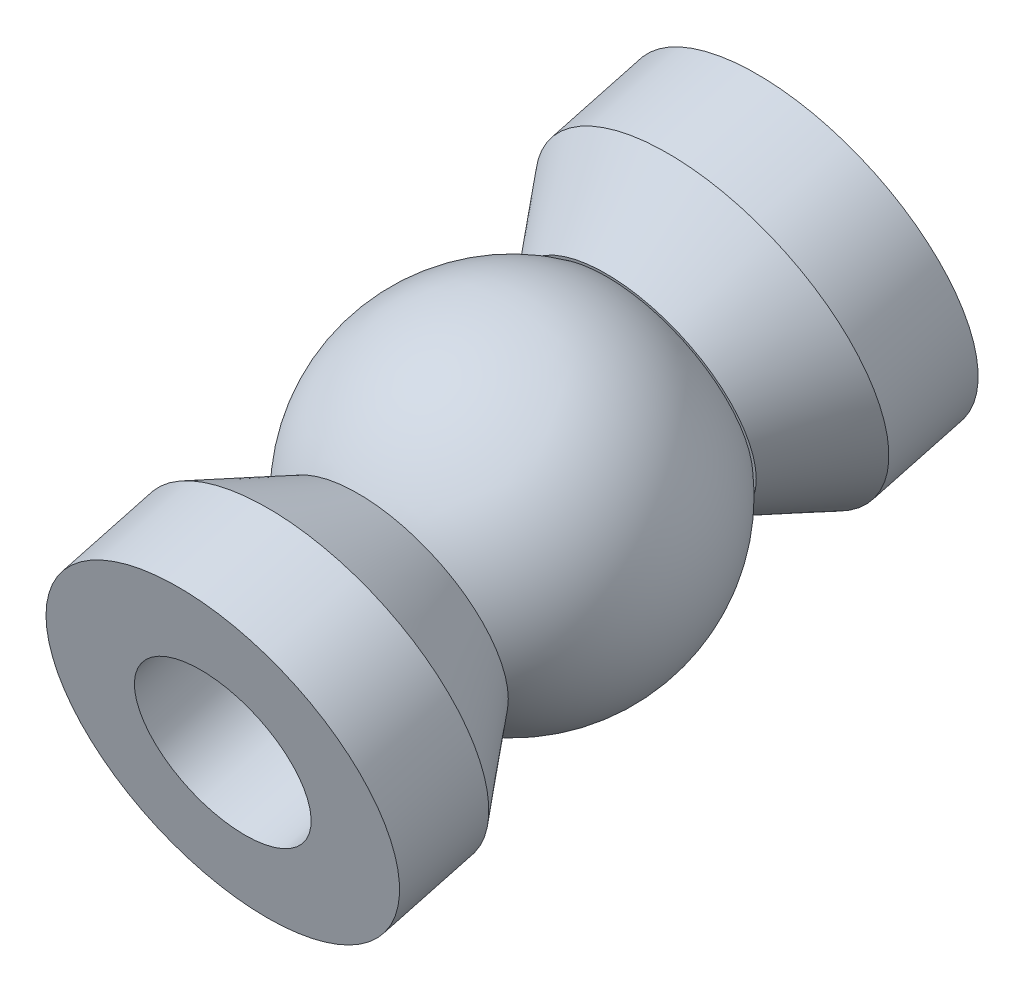
SolidWorks part; units mm, degrees
material "Alloy Steel"
ref_plane "X-Y Datum" through (0, 0, 0) normal (0, 0, 1) x (1, 0, 0)
ref_plane "X-Z Datum" through (0, 0, 0) normal (0, 1, 0) x (1, 0, 0)
ref_plane "Y-Z Datum" through (0, 0, 0) normal (1, 0, 0) x (0, 0, -1)
sketch "Sketch1" plane through (0, 0, 0) normal (1, 0, 0) x (0, 0, -1)
  line L0 (25.353, -33.2172) -> (-48270.9384, -12974.1695) construction
  line L1 (32.2801, -31.5492) -> (-12908.6721, 48264.7421) construction
  line L2 (21.7638, -29.1038) -> (17.1636, -30.3364) construction
  line L3 (23.1427, -40.3834) -> (26.4549, -39.4959)
  line L4 (26.4549, -39.4959) -> (28.7504, -36.7772)
  line L5 (28.7504, -36.7772) -> (28.7199, -36.6633)
  line L6 (23.1427, -40.3834) -> (21.4992, -34.2498)
  line L7 (28.4546, -35.6731) -> (37.655, -33.2079)
  line L10 (21.4992, -34.2498) -> (27.6328, -32.6063)
  line L11 (28.4546, -35.6731) -> (27.6328, -32.6063)
  line L12 (28.7199, -36.6633) -> (28.4546, -35.6731) construction
  line L13 (37.9509, -34.3119) -> (37.9204, -34.1981)
  line L14 (37.655, -33.2079) -> (36.8333, -30.1411)
  line L15 (42.9669, -28.4976) -> (36.8333, -30.1411)
  line L16 (44.6104, -34.6312) -> (42.9669, -28.4976)
  line L17 (44.6104, -34.6312) -> (41.2983, -35.5187)
  line L18 (41.2983, -35.5187) -> (37.9509, -34.3119)
  arc A0 (28.7199, -36.6633) -> (37.9204, -34.1981) centre (32.2331, -31.3737) ccw
  point P9 (32.2331, -31.3737)
  point P23 (33.0548, -34.4405)
  dimension "D1" = 12.7
  dimension "D2" = 6.35
  dimension "D3" = 9.525
  dimension "D4" = 22.225
  dimension "D5" = 6.35
  dimension "D6" = 3.429
  dimension "D7" = 4.318
revolve "Revolve1" add sketch "Sketch1" angle 360 about L10
hole_wizard "1/4 Clearance Hole1" positions "Sketch2" profile "Sketch3" hole size "1/4" standard "ANSI Inch" end condition through all
sketch "Sketch2" plane through (0, 3.0805, -11.4966) normal (0, -0.2588, 0.9659) x (1, 0, 0)
  point P0 (0, -38.6472)
sketch "Sketch3" plane through (0, -34.2498, -21.4992) normal (1, 0, 0) x (0, -0.9659, -0.2588)
  line L0 (0, 0) -> (0, 25.4)
  line L1 (0, 25.4) -> (3.175, 25.4)
  line L2 (3.175, 25.4) -> (3.175, 0)
  line L5 (3.175, 0) -> (0, 0)
  line L11 (0, -6.35) -> (0, 107.95) construction
  dimension "Thru Hole Dia." = 6.35
  dimension "Thru Hole Depth" = 25.4
